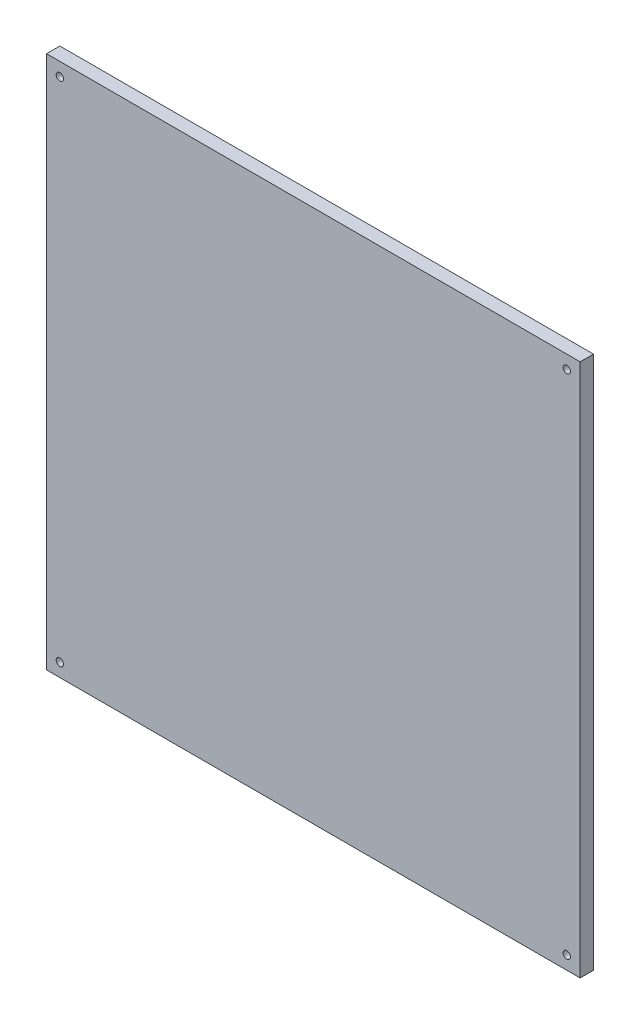
SolidWorks part; units mm, degrees
ref_plane "Plan de face" through (0, 0, 0) normal (0, 0, 1) x (1, 0, 0)
ref_plane "Plan de dessus" through (0, 0, 0) normal (0, 1, 0) x (1, 0, 0)
ref_plane "Plan de droite" through (0, 0, 0) normal (1, 0, 0) x (0, 0, -1)
sketch "Esquisse1" plane through (0, 0, 0) normal (0, 0, 1) x (1, 0, 0)
  line L4 (-200, 200) -> (-200, -200)
  line L5 (-200, -200) -> (200, -200)
  line L6 (200, -200) -> (200, 200)
  line L7 (200, 200) -> (-200, 200)
  line L8 (-200, 200) -> (-200, -200)
  line L9 (-200, -200) -> (200, -200)
  line L10 (200, -200) -> (200, 200)
  line L11 (200, 200) -> (-200, 200)
  dimension "D1" = 0
extrude "Boss.-Extru.1" add sketch "Esquisse1" along normal blind 10
hole_wizard "Dégagement M51" positions "Esquisse3" profile "Esquisse2" hole size "M5" standard "Din"
sketch "Esquisse3" plane through (0, 0, 10) normal (0, 0, 1) x (1, 0, 0)
  point P0 (190, 190)
  point P3 (-190, 190)
  point P6 (-190, -190)
  point P8 (190, -190)
sketch "Esquisse2" plane through (190, 190, 10) normal (1, 0, 0) x (0, -1, 0)
  line L0 (0, 0) -> (0, 16)
  line L1 (0, 16) -> (2.75, 16)
  line L2 (2.75, 16) -> (2.75, 0)
  line L5 (2.75, 0) -> (0, 0)
  line L10 (0, 16) -> (-2.75, 16) construction
  line L11 (0, -6.35) -> (0, 107.95) construction
  dimension "Diamètre du perçage" = 5.5
  dimension "Profondeur du perçage" = 16
  dimension "Angle de pointe" = 180
